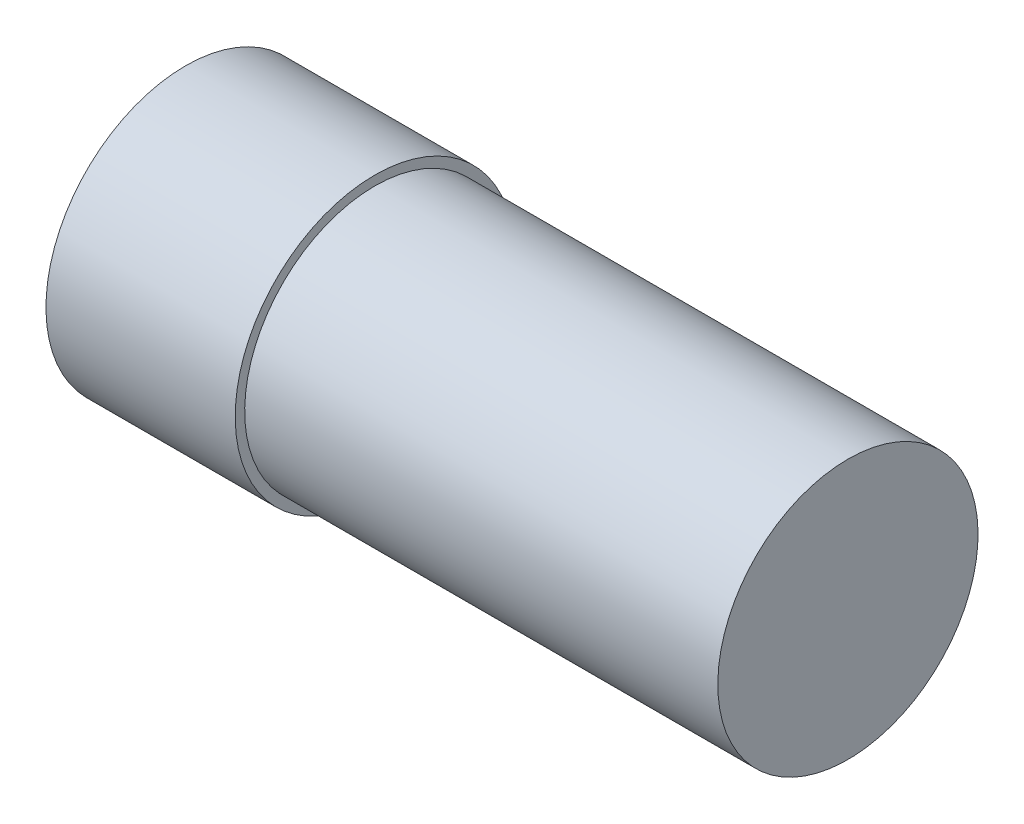
SolidWorks part; units mm, degrees
material "Acier allié"
ref_plane "Plan de face" through (0, 0, 0) normal (0, 0, 1) x (1, 0, 0)
ref_plane "Plan de dessus" through (0, 0, 0) normal (0, 1, 0) x (1, 0, 0)
ref_plane "Plan de droite" through (0, 0, 0) normal (1, 0, 0) x (0, 0, -1)
sketch "Esquisse1" plane through (0, 0, 0) normal (0, 0, 1) x (1, 0, 0)
  line L0 (0, 0) -> (0, 29.5)
  line L1 (0, 29.5) -> (40, 29.5)
  line L2 (40, 29.5) -> (40, 27.5)
  line L3 (40, 27.5) -> (140, 27.5)
  line L4 (140, 27.5) -> (140, 0)
  line L5 (140, 0) -> (0, 0)
  dimension "D1" = 29.5
  dimension "D2" = 27.5
  dimension "D3" = 140
  dimension "D4" = 40
revolve "Révolution1" add sketch "Esquisse1" angle 360 about L5
